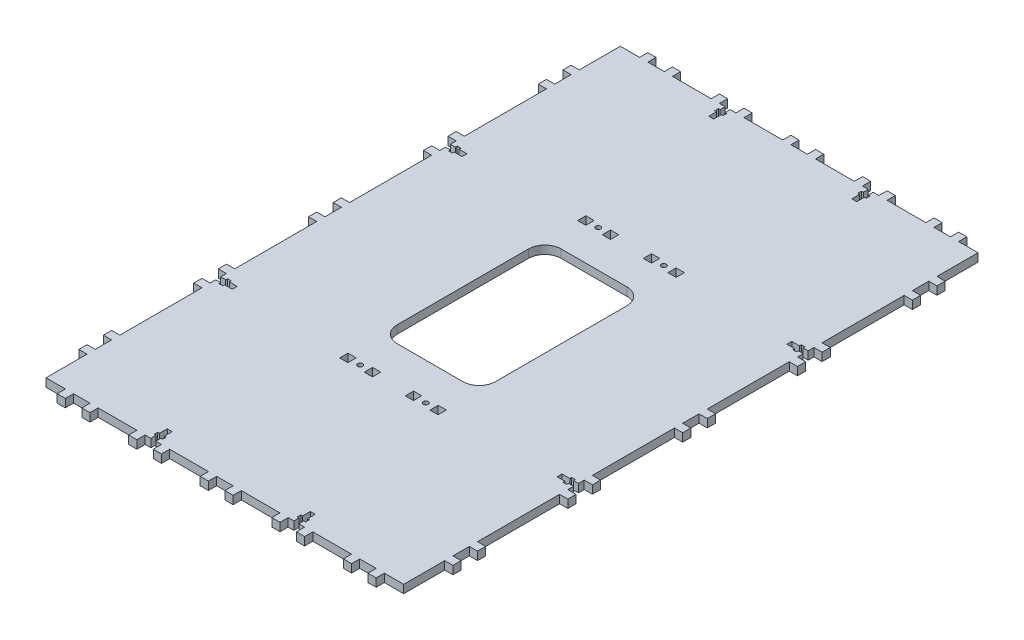
SolidWorks part; units mm, degrees
ref_plane "Front Plane" through (0, 0, 0) normal (0, 0, 1) x (1, 0, 0)
ref_plane "Top Plane" through (0, 0, 0) normal (0, 1, 0) x (1, 0, 0)
ref_plane "Right Plane" through (0, 0, 0) normal (1, 0, 0) x (0, 0, -1)
sketch "Sketch1" plane through (0, 0, 0) normal (0, 1, 0) x (1, 0, 0)
  line L0 (0, 0) -> (0, 175) construction
  line L64 (-30, 72.525) -> (30, 72.525) construction
  line L82 (-10, 75.05) -> (-10, 70)
  line L83 (-20, 50) -> (20, 50)
  line L84 (-30, 40) -> (-30, -40)
  line L85 (-20, -50) -> (20, -50)
  line L86 (30, 40) -> (30, -40)
  line L87 (-30, 50) -> (30, -50) construction
  line L88 (-30, -50) -> (30, 50) construction
  line L89 (30, 75.05) -> (25, 75.05)
  line L90 (30, 75.05) -> (30, 70)
  line L91 (30, 70) -> (25, 70)
  line L92 (10, 75.05) -> (10, 70)
  line L94 (109, -175) -> (109, -150)
  line L95 (-30, 70) -> (-25, 70)
  line L96 (-109, -175) -> (-97.2, -175)
  line L97 (-109, -175) -> (-109, -150)
  line L98 (-30, 75.05) -> (-25, 75.05)
  line L99 (-30, 75.05) -> (-30, 70)
  line L100 (56.5463, 0) -> (-43.4482, 0) construction
  line L109 (15, 75.05) -> (15, 70)
  line L110 (25, 75.05) -> (25, 70)
  line L111 (15, 75.05) -> (10, 75.05)
  line L114 (15, 70) -> (10, 70)
  line L115 (-15, 75.05) -> (-15, 70)
  line L116 (-25, 75.05) -> (-25, 70)
  line L117 (-15, 75.05) -> (-10, 75.05)
  line L118 (-109, -175) -> (109, 175) construction
  line L119 (-109, 175) -> (109, -175) construction
  line L120 (-15, 70) -> (-10, 70)
  line L121 (-109, 175) -> (-97.2, 175)
  line L122 (0, 0) -> (0, -206.09) construction
  line L123 (0, 0) -> (179.3861, 0) construction
  line L124 (0, -175) -> (0, -163.7792) construction
  line L125 (19.5, -175) -> (10, -175)
  line L126 (-5, -180) -> (-10, -180)
  line L127 (-10, -180) -> (-10, -175)
  line L128 (-5, -180) -> (-5, -175)
  line L129 (-15, -70) -> (-10, -70)
  line L130 (-15, -75.05) -> (-10, -75.05)
  line L131 (-25, -75.05) -> (-25, -70)
  line L132 (-15, -75.05) -> (-15, -70)
  line L133 (15, -70) -> (10, -70)
  line L134 (15, -75.05) -> (10, -75.05)
  line L135 (25, -75.05) -> (25, -70)
  line L136 (15, -75.05) -> (15, -70)
  line L137 (-30, -75.05) -> (-30, -70)
  line L138 (-30, -75.05) -> (-25, -75.05)
  line L139 (-30, -70) -> (-25, -70)
  line L140 (10, -75.05) -> (10, -70)
  line L141 (30, -70) -> (25, -70)
  line L142 (30, -75.05) -> (30, -70)
  line L143 (30, -75.05) -> (25, -75.05)
  line L144 (-10, -75.05) -> (-10, -70)
  line L145 (-19.5, -175) -> (-10, -175)
  line L146 (5, -175) -> (5, -180)
  line L147 (5, -180) -> (10, -180)
  line L148 (10, -180) -> (10, -175)
  line L149 (43.6, -175) -> (43.6, -177.9498) construction
  line L150 (42.1, -175) -> (38.6, -175)
  line L151 (38.6, -180) -> (33.6, -180)
  line L152 (33.6, -180) -> (33.6, -175)
  line L153 (38.6, -180) -> (38.6, -175)
  line L154 (45.1, -175) -> (48.6, -175)
  line L155 (48.6, -175) -> (48.6, -180)
  line L156 (48.6, -180) -> (53.6, -180)
  line L157 (53.6, -180) -> (53.6, -175)
  line L158 (87.2, -175) -> (87.2, -176.7176) construction
  line L159 (123.5, -175) -> (97.2, -175)
  line L160 (82.2, -180) -> (77.2, -180)
  line L161 (77.2, -180) -> (77.2, -175)
  line L162 (82.2, -180) -> (82.2, -175)
  line L163 (50.9, -175) -> (77.2, -175)
  line L164 (92.2, -175) -> (92.2, -180)
  line L165 (92.2, -180) -> (97.2, -180)
  line L166 (97.2, -180) -> (97.2, -175)
  line L167 (42.1, -175) -> (45.1, -175) construction
  line L168 (45.1, -175) -> (45.1, -172)
  line L169 (45.1, -169.7) -> (46.2, -169.7)
  line L170 (41, -172) -> (41, -169.7)
  line L171 (46.2, -172) -> (45.1, -172)
  line L172 (45.1, -169.7) -> (45.1, -165)
  line L173 (45.1, -165) -> (42.1, -165)
  line L174 (42.1, -165) -> (42.1, -169.7)
  line L175 (42.1, -172) -> (41, -172)
  line L176 (46.2, -169.7) -> (46.2, -172)
  line L177 (41, -169.7) -> (42.1, -169.7)
  line L178 (42.1, -172) -> (42.1, -175)
  line L179 (43.6, -165) -> (43.6, -175) construction
  line L180 (19.5, -175) -> (10, -175) construction
  line L181 (109, -140) -> (144.5683, -140) construction
  line L182 (109, -131.5) -> (109, -145)
  line L183 (114, -145) -> (114, -150)
  line L184 (114, -150) -> (109, -150)
  line L185 (114, -145) -> (109, -145)
  line L186 (109, -148.5) -> (109, -135)
  line L187 (109, -135) -> (114, -135)
  line L188 (114, -135) -> (114, -130)
  line L189 (114, -130) -> (109, -130)
  line L190 (109, -131.5) -> (109, -148.5) construction
  line L191 (109, -130) -> (109, -80)
  line L192 (0, -165) -> (0, -175) construction
  line L193 (123.5, -175) -> (97.2, -175) construction
  line L194 (109, -145) -> (109, -135)
  line L195 (109, 10) -> (109, 60)
  line L196 (109, -5) -> (109, 5)
  line L197 (109, -60) -> (109, -10)
  line L198 (109, -75) -> (109, -65)
  line L199 (82.2, -175) -> (92.2, -175)
  line L200 (97.2, -175) -> (109, -175)
  line L201 (38.6, -175) -> (48.6, -175)
  line L202 (53.6, -175) -> (77.2, -175)
  line L203 (-5, -175) -> (5, -175)
  line L204 (10, -175) -> (33.6, -175)
  line L205 (87.2, -165) -> (87.2, -175) construction
  line L206 (109, -70) -> (138.8281, -70) construction
  line L207 (109, -71.5) -> (109, -75)
  line L208 (114, -75) -> (114, -80)
  line L209 (114, -80) -> (109, -80)
  line L210 (114, -75) -> (109, -75)
  line L211 (109, -68.5) -> (109, -65)
  line L212 (109, -65) -> (114, -65)
  line L213 (114, -65) -> (114, -60)
  line L214 (114, -60) -> (109, -60)
  line L215 (109, -71.5) -> (109, -68.5) construction
  line L216 (109, -68.5) -> (106, -68.5)
  line L217 (103.7, -68.5) -> (103.7, -67.4)
  line L218 (106, -72.6) -> (103.7, -72.6)
  line L219 (106, -67.4) -> (106, -68.5)
  line L220 (103.7, -68.5) -> (99, -68.5)
  line L221 (99, -68.5) -> (99, -71.5)
  line L222 (99, -71.5) -> (103.7, -71.5)
  line L223 (106, -71.5) -> (106, -72.6)
  line L224 (103.7, -67.4) -> (106, -67.4)
  line L225 (103.7, -72.6) -> (103.7, -71.5)
  line L226 (106, -71.5) -> (109, -71.5)
  line L227 (99, -70) -> (109, -70) construction
  line L228 (109, 0) -> (144.5683, 0) construction
  line L229 (109, 8.5) -> (109, -5)
  line L230 (114, -5) -> (114, -10)
  line L231 (114, -10) -> (109, -10)
  line L232 (114, -5) -> (109, -5)
  line L233 (109, -8.5) -> (109, 5)
  line L234 (109, 5) -> (114, 5)
  line L235 (114, 5) -> (114, 10)
  line L236 (114, 10) -> (109, 10)
  line L237 (109, 8.5) -> (109, -8.5) construction
  line L238 (99, 70) -> (109, 70) construction
  line L239 (109, 71.5) -> (109, 68.5) construction
  line L240 (109, 70) -> (138.8281, 70) construction
  line L241 (109, 131.5) -> (109, 148.5) construction
  line L242 (109, 140) -> (144.5683, 140) construction
  line L243 (106, 71.5) -> (109, 71.5)
  line L244 (103.7, 72.6) -> (103.7, 71.5)
  line L245 (103.7, 67.4) -> (106, 67.4)
  line L246 (106, 71.5) -> (106, 72.6)
  line L247 (99, 71.5) -> (103.7, 71.5)
  line L248 (99, 68.5) -> (99, 71.5)
  line L249 (120, 0) -> (109, 0) construction
  line L250 (103.7, 68.5) -> (99, 68.5)
  line L251 (106, 67.4) -> (106, 68.5)
  line L252 (106, 72.6) -> (103.7, 72.6)
  line L253 (103.7, 68.5) -> (103.7, 67.4)
  line L254 (109, 68.5) -> (106, 68.5)
  line L255 (114, 60) -> (109, 60)
  line L256 (114, 65) -> (114, 60)
  line L257 (109, 65) -> (114, 65)
  line L258 (109, 68.5) -> (109, 65)
  line L259 (114, 75) -> (109, 75)
  line L260 (114, 80) -> (109, 80)
  line L261 (114, 75) -> (114, 80)
  line L262 (109, 71.5) -> (109, 75)
  line L263 (109, 75) -> (109, 65)
  line L264 (109, 145) -> (109, 135)
  line L265 (114, 130) -> (109, 130)
  line L266 (114, 135) -> (114, 130)
  line L267 (109, 135) -> (114, 135)
  line L268 (109, 148.5) -> (109, 135)
  line L269 (114, 145) -> (109, 145)
  line L270 (114, 150) -> (109, 150)
  line L271 (114, 145) -> (114, 150)
  line L272 (109, 131.5) -> (109, 145)
  line L273 (-120, 0) -> (-109, 0) construction
  line L274 (-109, 140) -> (-144.5683, 140) construction
  line L275 (-109, 131.5) -> (-109, 148.5) construction
  line L276 (-109, 70) -> (-138.8281, 70) construction
  line L277 (-109, 71.5) -> (-109, 68.5) construction
  line L278 (-99, 70) -> (-109, 70) construction
  line L279 (-109, 8.5) -> (-109, -8.5) construction
  line L280 (-109, 0) -> (-144.5683, 0) construction
  line L281 (-99, -70) -> (-109, -70) construction
  line L282 (-109, -71.5) -> (-109, -68.5) construction
  line L283 (-109, -70) -> (-138.8281, -70) construction
  line L284 (-109, -131.5) -> (-109, -148.5) construction
  line L285 (-109, -140) -> (-144.5683, -140) construction
  line L286 (-109, 131.5) -> (-109, 145)
  line L287 (-114, 145) -> (-114, 150)
  line L288 (-114, 150) -> (-109, 150)
  line L289 (-114, 145) -> (-109, 145)
  line L290 (-109, 148.5) -> (-109, 135)
  line L291 (-109, 135) -> (-114, 135)
  line L292 (-114, 135) -> (-114, 130)
  line L293 (-114, 130) -> (-109, 130)
  line L294 (-109, 145) -> (-109, 135)
  line L295 (-109, 75) -> (-109, 65)
  line L296 (-109, 71.5) -> (-109, 75)
  line L297 (-114, 75) -> (-114, 80)
  line L298 (-114, 80) -> (-109, 80)
  line L299 (-114, 75) -> (-109, 75)
  line L300 (-109, 68.5) -> (-109, 65)
  line L301 (-109, 65) -> (-114, 65)
  line L302 (-114, 65) -> (-114, 60)
  line L303 (-114, 60) -> (-109, 60)
  line L304 (-109, 68.5) -> (-106, 68.5)
  line L305 (-103.7, 68.5) -> (-103.7, 67.4)
  line L306 (-106, 72.6) -> (-103.7, 72.6)
  line L307 (-106, 67.4) -> (-106, 68.5)
  line L308 (-103.7, 68.5) -> (-99, 68.5)
  line L309 (-99, 68.5) -> (-99, 71.5)
  line L310 (-99, 71.5) -> (-103.7, 71.5)
  line L311 (-106, 71.5) -> (-106, 72.6)
  line L312 (-103.7, 67.4) -> (-106, 67.4)
  line L313 (-103.7, 72.6) -> (-103.7, 71.5)
  line L314 (-106, 71.5) -> (-109, 71.5)
  line L315 (-114, 10) -> (-109, 10)
  line L316 (-114, 5) -> (-114, 10)
  line L317 (-109, 5) -> (-114, 5)
  line L318 (-109, -8.5) -> (-109, 5)
  line L319 (-114, -5) -> (-109, -5)
  line L320 (-114, -10) -> (-109, -10)
  line L321 (-114, -5) -> (-114, -10)
  line L322 (-109, 8.5) -> (-109, -5)
  line L323 (-106, -71.5) -> (-109, -71.5)
  line L324 (-103.7, -72.6) -> (-103.7, -71.5)
  line L325 (-103.7, -67.4) -> (-106, -67.4)
  line L326 (-106, -71.5) -> (-106, -72.6)
  line L327 (-99, -71.5) -> (-103.7, -71.5)
  line L328 (-99, -68.5) -> (-99, -71.5)
  line L329 (-103.7, -68.5) -> (-99, -68.5)
  line L330 (-106, -67.4) -> (-106, -68.5)
  line L331 (-106, -72.6) -> (-103.7, -72.6)
  line L332 (-103.7, -68.5) -> (-103.7, -67.4)
  line L333 (-109, -68.5) -> (-106, -68.5)
  line L334 (-114, -60) -> (-109, -60)
  line L335 (-114, -65) -> (-114, -60)
  line L336 (-109, -65) -> (-114, -65)
  line L337 (-109, -68.5) -> (-109, -65)
  line L338 (-114, -75) -> (-109, -75)
  line L339 (-114, -80) -> (-109, -80)
  line L340 (-114, -75) -> (-114, -80)
  line L341 (-109, -71.5) -> (-109, -75)
  line L342 (-109, -75) -> (-109, -65)
  line L343 (-109, -5) -> (-109, 5)
  line L344 (-109, -145) -> (-109, -135)
  line L345 (-114, -130) -> (-109, -130)
  line L346 (-114, -135) -> (-114, -130)
  line L347 (-109, -135) -> (-114, -135)
  line L348 (-109, -148.5) -> (-109, -135)
  line L349 (-114, -145) -> (-109, -145)
  line L350 (-114, -150) -> (-109, -150)
  line L351 (-114, -145) -> (-114, -150)
  line L352 (-109, -131.5) -> (-109, -145)
  line L353 (-87.2, -165) -> (-87.2, -175) construction
  line L354 (-123.5, -175) -> (-97.2, -175) construction
  line L355 (-43.6, -165) -> (-43.6, -175) construction
  line L356 (-87.2, -175) -> (-87.2, -176.7176) construction
  line L357 (-42.1, -175) -> (-45.1, -175) construction
  line L358 (-53.6, -175) -> (-77.2, -175)
  line L359 (-43.6, -175) -> (-43.6, -177.9498) construction
  line L360 (-82.2, -175) -> (-92.2, -175)
  line L361 (-38.6, -175) -> (-48.6, -175)
  line L362 (-42.1, -172) -> (-42.1, -175)
  line L363 (-41, -169.7) -> (-42.1, -169.7)
  line L364 (-46.2, -169.7) -> (-46.2, -172)
  line L365 (-42.1, -172) -> (-41, -172)
  line L366 (-42.1, -165) -> (-42.1, -169.7)
  line L367 (-97.2, -180) -> (-97.2, -175)
  line L368 (-92.2, -180) -> (-97.2, -180)
  line L369 (-92.2, -175) -> (-92.2, -180)
  line L370 (-53.6, -175) -> (-77.2, -175)
  line L371 (-82.2, -180) -> (-82.2, -175)
  line L372 (-77.2, -180) -> (-77.2, -175)
  line L373 (-82.2, -180) -> (-77.2, -180)
  line L374 (-123.5, -175) -> (-97.2, -175)
  line L375 (-45.1, -165) -> (-42.1, -165)
  line L376 (-45.1, -169.7) -> (-45.1, -165)
  line L377 (-46.2, -172) -> (-45.1, -172)
  line L378 (-41, -172) -> (-41, -169.7)
  line L379 (-45.1, -169.7) -> (-46.2, -169.7)
  line L380 (-45.1, -175) -> (-45.1, -172)
  line L381 (-53.6, -180) -> (-53.6, -175)
  line L382 (-48.6, -180) -> (-53.6, -180)
  line L383 (-48.6, -175) -> (-48.6, -180)
  line L384 (-45.1, -175) -> (-48.6, -175)
  line L385 (-38.6, -180) -> (-38.6, -175)
  line L386 (-33.6, -180) -> (-33.6, -175)
  line L387 (-38.6, -180) -> (-33.6, -180)
  line L388 (-42.1, -175) -> (-38.6, -175)
  line L389 (-43.6, 175) -> (-43.6, 177.9498) construction
  line L390 (-42.1, 175) -> (-45.1, 175) construction
  line L391 (-87.2, 175) -> (-87.2, 176.7176) construction
  line L392 (-43.6, 165) -> (-43.6, 175) construction
  line L393 (-123.5, 175) -> (-97.2, 175) construction
  line L394 (-87.2, 165) -> (-87.2, 175) construction
  line L395 (87.2, 165) -> (87.2, 175) construction
  line L396 (123.5, 175) -> (97.2, 175) construction
  line L397 (0, 165) -> (0, 175) construction
  line L398 (19.5, 175) -> (10, 175) construction
  line L399 (43.6, 165) -> (43.6, 175) construction
  line L400 (42.1, 175) -> (45.1, 175) construction
  line L401 (87.2, 175) -> (87.2, 176.7176) construction
  line L402 (43.6, 175) -> (43.6, 177.9498) construction
  line L403 (0, 175) -> (0, 163.7792) construction
  line L404 (-42.1, 175) -> (-38.6, 175)
  line L405 (-38.6, 180) -> (-33.6, 180)
  line L406 (-33.6, 180) -> (-33.6, 175)
  line L407 (-38.6, 180) -> (-38.6, 175)
  line L408 (-45.1, 175) -> (-48.6, 175)
  line L409 (-48.6, 175) -> (-48.6, 180)
  line L410 (-48.6, 180) -> (-53.6, 180)
  line L411 (-53.6, 180) -> (-53.6, 175)
  line L412 (-45.1, 175) -> (-45.1, 172)
  line L413 (-45.1, 169.7) -> (-46.2, 169.7)
  line L414 (-41, 172) -> (-41, 169.7)
  line L415 (-46.2, 172) -> (-45.1, 172)
  line L416 (-45.1, 169.7) -> (-45.1, 165)
  line L417 (-45.1, 165) -> (-42.1, 165)
  line L418 (-123.5, 175) -> (-97.2, 175)
  line L419 (-82.2, 180) -> (-77.2, 180)
  line L420 (-77.2, 180) -> (-77.2, 175)
  line L421 (-82.2, 180) -> (-82.2, 175)
  line L422 (-53.6, 175) -> (-77.2, 175)
  line L423 (-92.2, 175) -> (-92.2, 180)
  line L424 (-92.2, 180) -> (-97.2, 180)
  line L425 (-97.2, 180) -> (-97.2, 175)
  line L426 (-42.1, 165) -> (-42.1, 169.7)
  line L427 (-42.1, 172) -> (-41, 172)
  line L428 (-46.2, 169.7) -> (-46.2, 172)
  line L429 (-41, 169.7) -> (-42.1, 169.7)
  line L430 (-42.1, 172) -> (-42.1, 175)
  line L431 (-38.6, 175) -> (-48.6, 175)
  line L432 (-82.2, 175) -> (-92.2, 175)
  line L433 (-53.6, 175) -> (-77.2, 175)
  line L434 (10, 175) -> (33.6, 175)
  line L435 (-5, 175) -> (5, 175)
  line L436 (53.6, 175) -> (77.2, 175)
  line L437 (38.6, 175) -> (48.6, 175)
  line L438 (82.2, 175) -> (92.2, 175)
  line L439 (42.1, 172) -> (42.1, 175)
  line L440 (41, 169.7) -> (42.1, 169.7)
  line L441 (46.2, 169.7) -> (46.2, 172)
  line L442 (42.1, 172) -> (41, 172)
  line L443 (42.1, 165) -> (42.1, 169.7)
  line L444 (45.1, 165) -> (42.1, 165)
  line L445 (45.1, 169.7) -> (45.1, 165)
  line L446 (46.2, 172) -> (45.1, 172)
  line L447 (41, 172) -> (41, 169.7)
  line L448 (45.1, 169.7) -> (46.2, 169.7)
  line L449 (45.1, 175) -> (45.1, 172)
  line L450 (97.2, 180) -> (97.2, 175)
  line L451 (92.2, 180) -> (97.2, 180)
  line L452 (92.2, 175) -> (92.2, 180)
  line L453 (53.6, 175) -> (77.2, 175)
  line L454 (82.2, 180) -> (82.2, 175)
  line L455 (77.2, 180) -> (77.2, 175)
  line L456 (82.2, 180) -> (77.2, 180)
  line L457 (123.5, 175) -> (97.2, 175)
  line L458 (53.6, 180) -> (53.6, 175)
  line L459 (48.6, 180) -> (53.6, 180)
  line L460 (48.6, 175) -> (48.6, 180)
  line L461 (45.1, 175) -> (48.6, 175)
  line L462 (38.6, 180) -> (38.6, 175)
  line L463 (33.6, 180) -> (33.6, 175)
  line L464 (38.6, 180) -> (33.6, 180)
  line L465 (42.1, 175) -> (38.6, 175)
  line L466 (10, 180) -> (10, 175)
  line L467 (5, 180) -> (10, 180)
  line L468 (5, 175) -> (5, 180)
  line L469 (-19.5, 175) -> (-10, 175)
  line L470 (-5, 180) -> (-5, 175)
  line L471 (-10, 180) -> (-10, 175)
  line L472 (-5, 180) -> (-10, 180)
  line L473 (19.5, 175) -> (10, 175)
  line L474 (-92.2, 175) -> (-82.2, 175)
  line L475 (-77.2, 175) -> (-53.6, 175)
  line L476 (-48.6, 175) -> (-38.6, 175)
  line L477 (-33.6, 175) -> (-10, 175)
  line L478 (-5, 175) -> (5, 175)
  line L479 (10, 175) -> (33.6, 175)
  line L480 (38.6, 175) -> (48.6, 175)
  line L481 (53.6, 175) -> (77.2, 175)
  line L482 (82.2, 175) -> (92.2, 175)
  line L483 (97.2, 175) -> (109, 175)
  line L484 (-109, 150) -> (-109, 175)
  line L485 (-109, 135) -> (-109, 145)
  line L486 (-109, 80) -> (-109, 130)
  line L487 (-109, 65) -> (-109, 75)
  line L488 (-109, 10) -> (-109, 60)
  line L489 (-109, -5) -> (-109, 5)
  line L490 (-109, -60) -> (-109, -10)
  line L491 (-109, -75) -> (-109, -65)
  line L492 (-109, -130) -> (-109, -80)
  line L493 (-109, -145) -> (-109, -135)
  line L494 (-92.2, -175) -> (-82.2, -175)
  line L495 (-77.2, -175) -> (-53.6, -175)
  line L496 (-48.6, -175) -> (-38.6, -175)
  line L497 (-33.6, -175) -> (-10, -175)
  line L498 (109, 150) -> (109, 175)
  line L499 (109, 135) -> (109, 145)
  line L500 (109, 80) -> (109, 130)
  line L501 (109, 65) -> (109, 75)
  line L502 (-5, -175) -> (5, -175)
  line L503 (-10, -175) -> (-19.5, -175) construction
  line L504 (5, -175) -> (-5, -175)
  line L505 (5, -175) -> (-5, -175) construction
  line L506 (82.2, -175) -> (92.2, -175)
  line L507 (77.2, -175) -> (50.9, -175) construction
  line L508 (92.2, -175) -> (82.2, -175)
  line L509 (92.2, -175) -> (82.2, -175) construction
  line L510 (-77.2, -175) -> (-53.6, -175) construction
  line L511 (-82.2, -175) -> (-92.2, -175)
  line L512 (-92.2, -175) -> (-82.2, -175) construction
  line L513 (-92.2, -175) -> (-82.2, -175)
  line L514 (92.2, 175) -> (82.2, 175) construction
  line L515 (92.2, 175) -> (82.2, 175)
  line L516 (82.2, 175) -> (92.2, 175)
  line L517 (77.2, 175) -> (53.6, 175) construction
  line L518 (5, 175) -> (-5, 175) construction
  line L519 (5, 175) -> (-5, 175)
  line L520 (-5, 175) -> (5, 175)
  line L521 (-10, 175) -> (-19.5, 175) construction
  line L522 (-77.2, 175) -> (-53.6, 175) construction
  line L523 (-82.2, 175) -> (-92.2, 175)
  line L524 (-92.2, 175) -> (-82.2, 175) construction
  line L525 (-92.2, 175) -> (-82.2, 175)
  arc A0 (20, 50) -> (30, 40) centre (20, 40) cw
  arc A1 (-30, 40) -> (-20, 50) centre (-20, 40) cw
  arc A2 (-20, -50) -> (-30, -40) centre (-20, -40) cw
  arc A3 (20, -50) -> (30, -40) centre (20, -40) ccw
  circle A4 centre (20, 72.525) radius 1.5
  circle A6 centre (-20, 72.525) radius 1.5
  circle A7 centre (-20, -72.525) radius 1.5
  circle A8 centre (20, -72.525) radius 1.5
  point P37 (0, 0)
  point P89 (20, 72.525)
  dimension "D11" = 10
  dimension "D12" = 10
  dimension "D13" = 10
  dimension "D14" = 10
  dimension "D21" = 5
  dimension "D23" = 10
  dimension "D24" = 5
  dimension "D3" = 3
  dimension "D4" = 350
  dimension "D5" = 218
  dimension "D6" = 10
  dimension "D7" = 5
  dimension "D8" = 5
  dimension "D9" = 100
  dimension "D10" = 60
  dimension "D15" = 5.05
  dimension "D16" = 20
  dimension "D17" = 10
  dimension "D18" = 20
  dimension "D19" = 5
  dimension "D20" = 5
  dimension "D22" = 5
  dimension "D25" = 5
  dimension "D26" = 10
  dimension "D27" = 5
  dimension "D28" = 5
  dimension "D29" = 5.2
  dimension "D30" = 3
  dimension "D31" = 2.3
  dimension "D32" = 3
  dimension "D33" = 10
  dimension "D34" = 43.6
  dimension "D35" = 43.6
  dimension "D36" = 10
  dimension "D37" = 5
  dimension "D38" = 5
  dimension "D44" = 10
  dimension "D45" = 5
  dimension "D46" = 5
  dimension "D47" = 5.2
  dimension "D48" = 3
  dimension "D49" = 2.3
  dimension "D50" = 3
  dimension "D51" = 10
  dimension "D52" = 10
  dimension "D53" = 5
  dimension "D54" = 5
  dimension "D61" = 70
extrude "Boss-Extrude1" add sketch "Sketch1" along normal blind 5 contours L260 L500 L265 L266 L267 L264 L269 L271 L270 L498 L483 L450 L451 L452 L438 L454 L456 L455 L436 L458 L459 L460 L437 L449 L446 L441 L448 L445 L444 L443 L440 L447 L442 L439 L462 L464 L463 L434 L466 L467 L468 L435 L470 L472
